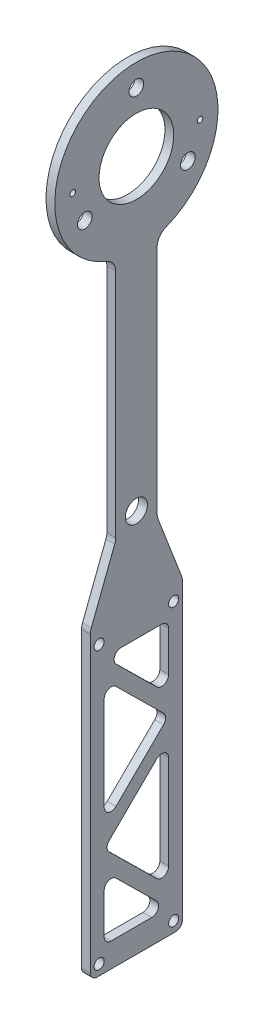
SolidWorks part; units mm, degrees
material "1060 Alloy"
ref_plane "Front Plane" through (0, 0, 0) normal (0, 0, 1) x (1, 0, 0)
ref_plane "Top Plane" through (0, 0, 0) normal (0, 1, 0) x (1, 0, 0)
ref_plane "Right Plane" through (0, 0, 0) normal (1, 0, 0) x (0, 0, -1)
sketch "Sketch1" plane through (0, 0, 0) normal (1, 0, 0) x (0, 0, -1)
  line L0 (-13.4747, 0) -> (13.4747, 0) construction
  line L1 (0, 0) -> (0, 35) construction
  line L2 (-13.4747, 0) -> (0, 35) construction
  line L3 (0, 35) -> (13.4747, 0) construction
  line L4 (13.4747, 0) -> (-13.4747, 0) construction
  line L5 (20.7574, -5) -> (-20.7574, -5)
  line L6 (-20.7574, -5) -> (0, 48.9165)
  line L7 (0, 48.9165) -> (20.7574, -5)
  line L8 (0, 35) -> (0, 146) construction
  line L9 (0, 35) -> (0, 146) construction
  line L12 (-7.5, 35) -> (-7.5, 146)
  line L13 (7.5, 35) -> (7.5, 146)
  line L14 (-7.5, 35) -> (-7.5, 29.4356)
  line L15 (7.5, 35) -> (7.5, 29.4356)
  line L16 (-13.4747, 0) -> (13.4747, 0) construction
  line L17 (-13.4747, 0) -> (-13.4747, -100) construction
  line L18 (13.4747, 0) -> (13.4747, -100) construction
  line L19 (-13.4747, -100) -> (13.4747, -100) construction
  line L20 (-20.7574, -5) -> (20.7574, -5)
  line L21 (-20.7574, -5) -> (-20.7574, -103.81)
  line L22 (20.7574, -5) -> (20.7574, -103.81)
  line L23 (-20.7574, -103.81) -> (20.7574, -103.81)
  circle A0 centre (-13.4747, 0) radius 1.8288
  circle A1 centre (0, 35) radius 4
  circle A2 centre (13.4747, 0) radius 1.8288
  circle A3 centre (0, 146) radius 3 construction
  arc A6 (-7.5, 35) -> (7.5, 35) centre (0, 35) ccw
  arc A7 (7.5, 146) -> (-7.5, 146) centre (0, 146) ccw
  circle A8 centre (-13.4747, -100) radius 1.8288
  circle A9 centre (13.4747, -100) radius 1.8288
  circle A10 centre (0, 146) radius 21.5 construction
  circle A11 centre (0, 167.5) radius 2.65
  circle A12 centre (-18.6195, 135.25) radius 2.65
  circle A13 centre (18.6195, 135.25) radius 2.65
  arc A14 (0, 167.5) -> (-18.6195, 135.25) centre (0, 146) ccw construction
  arc A15 (0, 167.5) -> (18.6195, 135.25) centre (0, 146) cw construction
  arc A16 (-18.6195, 135.25) -> (18.6195, 135.25) centre (0, 146) ccw construction
  circle A17 centre (0, 146) radius 13.5
  circle A18 centre (0, 146) radius 29.5
  point P4 (0, 0)
  point P14 (0, 90.5)
  point P34 (0, 146)
  dimension "D3" = 3.6576
  dimension "D4" = 8
  dimension "D7" = 6
  dimension "D11" = 43
  dimension "D12" = 5.3
  dimension "D13" = 27
  dimension "D14" = 59
  dimension "D1" = 26.9494
  dimension "D5" = 111
  dimension "D6" = 15
  dimension "D8" = 100
  dimension "D9" = 3.81
  dimension "D10" = 35
  dimension "D2" = 5
extrude "Boss-Extrude1" add sketch "Sketch1" along normal blind 3.175 contours L13 A18 L12 A17 A11 A12 A13 | L12 A18 L13 A17 | A18 L12 A6 L6 L7 L13 | L6 A6 L7 A1 | A6 L6 L5 L7 A2 A0 | A6 L14 L6 | A6 L7 L15 | L21 L23 L22 L5 A9 A8
sketch "Sketch2" plane through (3.175, 0, 0) normal (1, 0, 0) x (0, 0, -1)
  line L0 (-11.645, -5) -> (11.645, -5) construction
  line L1 (-11.645, -95) -> (11.645, -95) construction
  line L2 (11.645, -95) -> (11.645, -5) construction
  line L3 (-11.645, -95) -> (-11.645, -5) construction
  line L6 (11.645, -38.5118) -> (-11.645, -61.4882) construction
  line L7 (11.645, -5) -> (-11.645, -5)
  line L8 (-11.645, -5) -> (11.645, -27.9764)
  line L9 (11.645, -27.9764) -> (11.645, -5)
  line L10 (-11.645, -12.0236) -> (11.645, -35)
  line L11 (11.645, -35) -> (-11.645, -57.9764)
  line L12 (-11.645, -57.9764) -> (-11.645, -35)
  line L13 (-11.645, -35) -> (-11.645, -12.0236)
  line L14 (-11.645, -72.0236) -> (-11.645, -95)
  line L15 (-11.645, -95) -> (11.645, -95)
  line L16 (11.645, -95) -> (-11.645, -72.0236)
  line L17 (11.645, -42.0236) -> (11.645, -65)
  line L18 (11.645, -65) -> (11.645, -87.9764)
  line L19 (11.645, -87.9764) -> (-11.645, -65)
  line L20 (-11.645, -65) -> (11.645, -42.0236)
  line L21 (16.645, -1056.0877) -> (16.645, 48943.9123) construction
  line L22 (-16.645, -1060.2922) -> (-16.645, 48939.7078) construction
  line L23 (16.645, 29.4356) -> (-16.645, 29.4356) construction
  line L24 (-20.7574, -103.81) -> (-16.645, -103.81)
  line L25 (-20.7574, -103.81) -> (-20.7574, 29.4356)
  line L26 (-16.645, -103.81) -> (-16.645, 29.4356)
  line L27 (-20.7574, 29.4356) -> (-16.645, 29.4356)
  line L28 (-20.7574, -103.81) -> (20.7574, -103.81) construction
  line L29 (20.7574, -103.81) -> (16.645, -103.81)
  line L30 (20.7574, -103.81) -> (20.7574, 29.4356)
  line L31 (16.645, -103.81) -> (16.645, 29.4356)
  line L32 (20.7574, 29.4356) -> (16.645, 29.4356)
  circle A0 centre (13.4747, 0) radius 1.8288 construction
  circle A1 centre (13.4747, -100) radius 1.8288 construction
  point P6 (11.645, -50)
  point P10 (0, 29.4356)
  point P21 (0, -50)
  dimension "D1" = 33.29
  dimension "D2" = 5
  dimension "D3" = 5
  dimension "D4" = 5
  dimension "D5" = 5
  dimension "D6" = 2.5
  dimension "D8" = 5
  dimension "D7" = 2
extrude "Cut-Extrude1" cut sketch "Sketch2" against normal up to next
fillet "Fillet3" radius 2.5 14 edges at (1.5875, -57.9764, 11.645) (1.5875, -35, -11.645) (1.5875, -95, -11.645) (1.5875, -72.0236, 11.645) (1.5875, -95, 11.645) (1.5875, -27.9764, -11.645) (1.5875, -5, -11.645) (1.5875, -12.0236, 11.645) (1.5875, -5, 11.645) (1.5875, -87.9764, -11.645) (1.5875, -42.0236, -11.645) (1.5875, -65, 11.645) (1.5875, -103.81, -16.645) (1.5875, -103.81, 16.645)
fillet "Fillet4" radius 5 6 edges at (1.5875, 29.4356, -7.5) (1.5875, 29.4356, 7.5) (1.5875, 5.6818, 16.645) (1.5875, 5.6818, -16.645) (1.5875, 117.4693, -7.5) (1.5875, 117.4693, 7.5)
hole_wizard "M2.5x0.45 Tapped Hole1" positions "Sketch3" profile "Sketch4" tap size "M2.5x0.45" standard "ANSI Metric" end condition up to next
sketch "Sketch3" plane through (3.175, 0, 0) normal (1, 0, 0) x (0, 0, -1)
  line L0 (0, 167.5) -> (0, 146) construction
  line L2 (0, 146) -> (50000, 146) construction
  circle A0 centre (0, 146) radius 23.015 construction
  point P15 (-23.015, 146)
  point P17 (23.015, 146)
  dimension "D1" = 46.03
sketch "Sketch4" plane through (3.175, 146, -23.015) normal (0, 1, 0) x (0, 0, -1)
  line L0 (0, 0) -> (0, 3.175)
  line L1 (0, 3.175) -> (1.025, 3.175)
  line L2 (1.025, 3.175) -> (1.025, 0)
  line L5 (1.025, 0) -> (0, 0)
  line L11 (0, -6.35) -> (0, 107.95) construction
  dimension "Thru Tap Drill Dia." = 2.05
  dimension "Thru Tap Drill Depth" = 3.175
cosmetic thread "Hole Thread1" parameters "D2"=2.5
cosmetic thread "Hole Thread2" parameters "D2"=2.5
